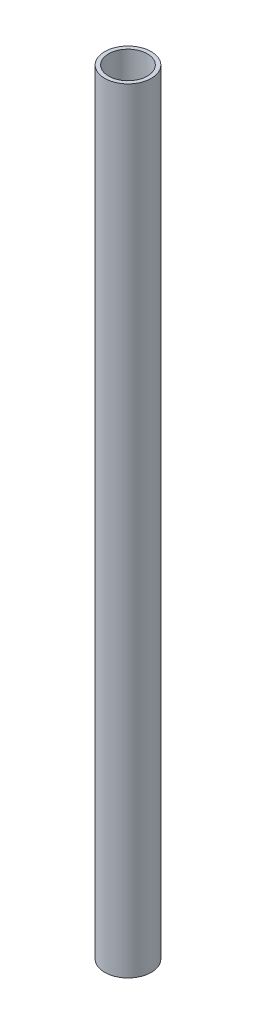
SolidWorks part; units mm, degrees
ref_plane "前视基准面" through (0, 0, 0) normal (0, 0, 1) x (1, 0, 0)
ref_plane "上视基准面" through (0, 0, 0) normal (0, 1, 0) x (1, 0, 0)
ref_plane "右视基准面" through (0, 0, 0) normal (1, 0, 0) x (0, 0, -1)
sketch "草图1" plane through (0, 0, 0) normal (0, 1, 0) x (1, 0, 0)
  circle A0 centre (0, 0) radius 5
  circle A1 centre (0, 0) radius 6
  dimension "D1" = 12
  dimension "D2" = 10
extrude "凸台-拉伸1" add sketch "草图1" along normal blind 200
